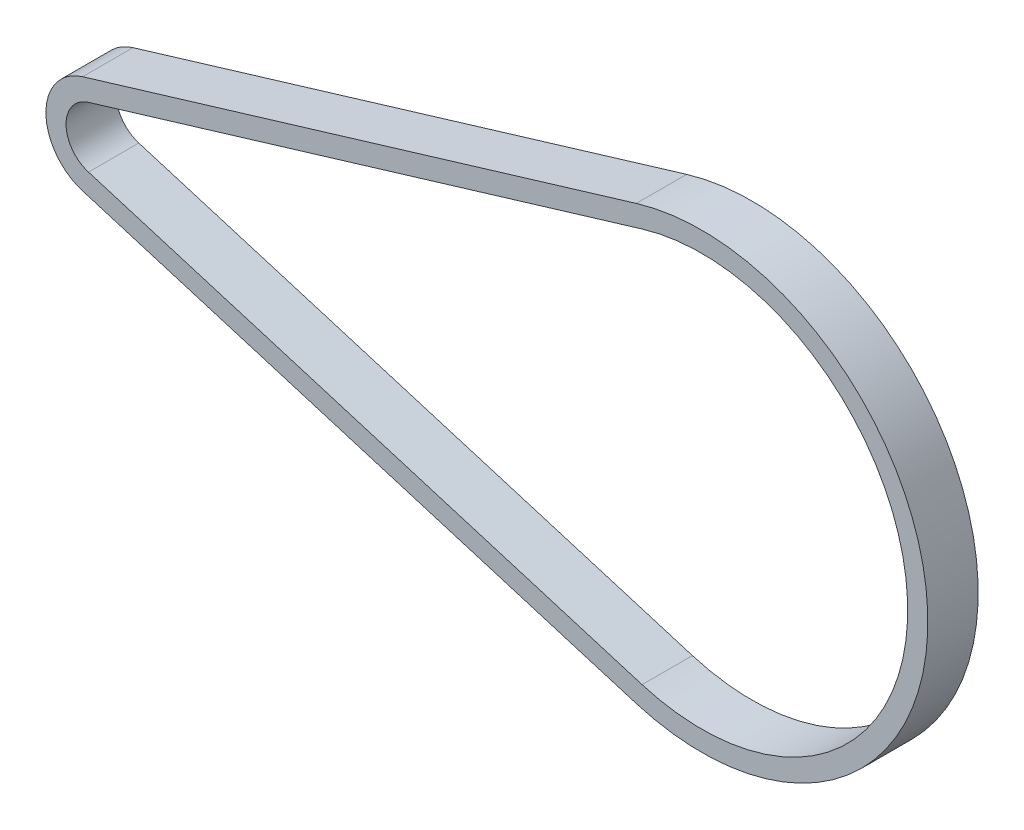
SolidWorks part; units mm, degrees
ref_plane "Front Plane" through (0, 0, 0) normal (0, 0, 1) x (1, 0, 0)
ref_plane "Top Plane" through (0, 0, 0) normal (0, 1, 0) x (1, 0, 0)
ref_plane "Right Plane" through (0, 0, 0) normal (1, 0, 0) x (0, 0, -1)
sketch "Sketch2" plane through (0, 0, 0) normal (0, 0, 1) x (1, 0, 0)
  line L0 (-24.9675, 15) -> (249.9868, 97.9845)
  line L1 (-24.9675, -15) -> (249.9868, -97.9845)
  arc A1 (249.9868, -97.9845) -> (249.9868, 97.9845) centre (279.5597, 0) ccw
  arc A2 (-24.9675, -15) -> (-24.9675, 15) centre (-20.4403, 0) cw
  dimension "D1" = 30
  dimension "D2" = 204.7
  dimension "D3" = 300
extrude "Extrude-Thin3" add sketch "Sketch2" along normal blind 25 thin thin type one direction wall 10
